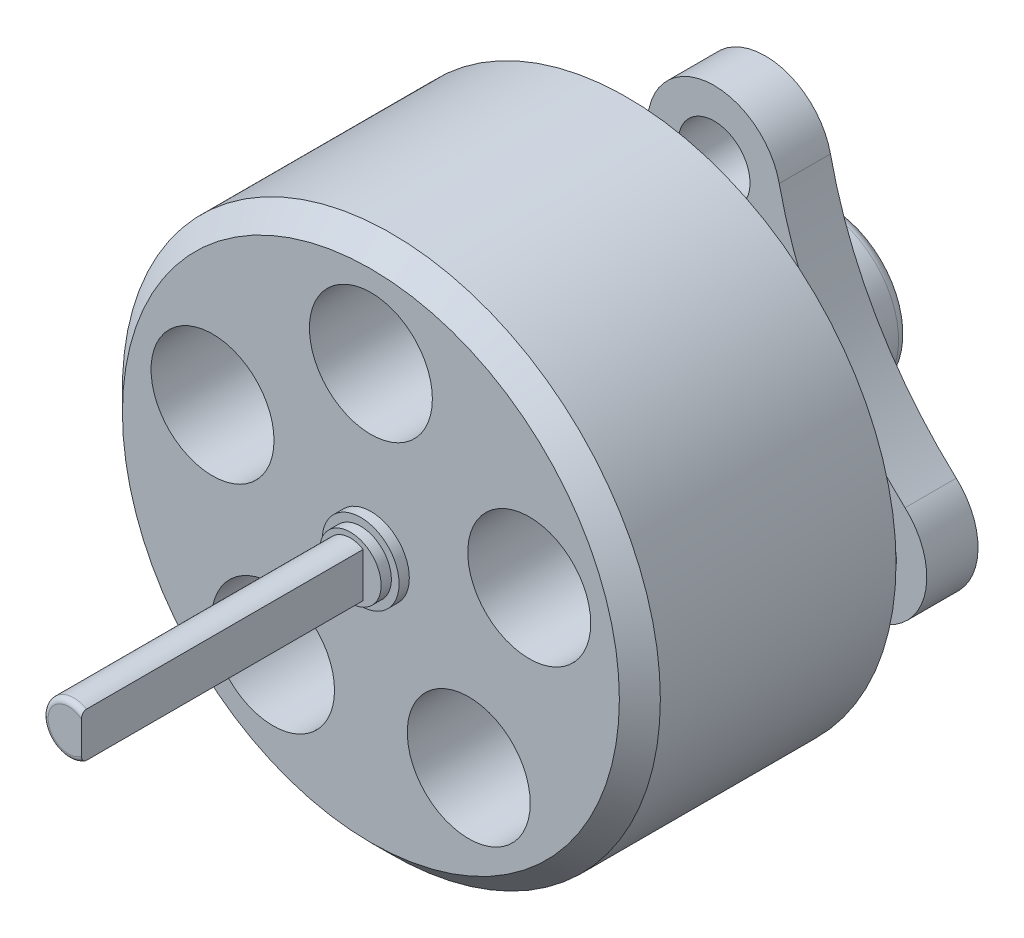
SolidWorks part; units mm, degrees
ref_plane "前视基准面" through (0, 0, 0) normal (0, 0, 1) x (1, 0, 0)
ref_plane "上视基准面" through (0, 0, 0) normal (0, 1, 0) x (1, 0, 0)
ref_plane "右视基准面" through (0, 0, 0) normal (1, 0, 0) x (0, 0, -1)
sketch "草图1" plane through (0, 0, 0) normal (0, 0, 1) x (1, 0, 0)
  circle A0 centre (0, 0) radius 5.25
  dimension "D1" = 10.5
extrude "凸台-拉伸1" add sketch "草图1" along normal blind 5
chamfer "倒角1" distance 0.4 angle 45 1 edges at (5.25, 0, 5)
sketch "草图2" plane through (0, 0, 5) normal (0, 0, 1) x (1, 0, 0)
  circle A0 centre (0, 3.25) radius 1.2
  circle A1 centre (0, 0) radius 3.25 construction
  circle A2 centre (3.0909, 1.0043) radius 1.2
  circle A3 centre (1.9103, -2.6293) radius 1.2
  circle A4 centre (-1.9103, -2.6293) radius 1.2
  circle A5 centre (-3.0909, 1.0043) radius 1.2
  point P15 (0, 0)
  dimension "D1" = 2.4
  dimension "D2" = 6.5
  dimension "D3" = 5
extrude "切除-拉伸1" cut sketch "草图2" against normal blind 2.5
sketch "草图3" plane through (0, 0, 5) normal (0, 0, 1) x (1, 0, 0)
  circle A0 centre (0, 0) radius 0.75
  dimension "D1" = 1.5
extrude "凸台-拉伸2" add sketch "草图3" along normal blind 0.2
sketch "草图4" plane through (0, 0, 5.2) normal (0, 0, 1) x (1, 0, 0)
  circle A0 centre (0, 0) radius 0.6
  dimension "D1" = 1.2
extrude "凸台-拉伸3" add sketch "草图4" along normal blind 0.2
sketch "草图5" plane through (0, 0, 5.4) normal (0, 0, 1) x (1, 0, 0)
  circle A0 centre (0, 0) radius 0.5
  dimension "D1" = 1
extrude "凸台-拉伸4" add sketch "草图5" along normal blind 5.5
fillet "圆角1" radius 0.1 1 edges at (0.5, 0, 10.9)
sketch "草图6" plane through (0, 0, 0) normal (0, 0, -1) x (-1, 0, 0)
  circle A0 centre (0, 0) radius 2.5
  dimension "D1" = 5
extrude "凸台-拉伸5" add sketch "草图6" along normal blind 1.7
sketch "草图7" plane through (0, 0, -1.7) normal (0, 0, -1) x (-1, 0, 0)
  arc A1 (3.2746, -0.4084) -> (3.1443, -1.0018) centre (0, 0) ccw construction
  arc A6 (1.2702, 3.5768) -> (-1.2702, 3.5768) centre (0, 3.3) ccw
  arc A7 (-3.7253, -0.6756) -> (-1.2702, 3.5768) centre (-9.157, 5.2953) ccw
  arc A8 (-3.7253, -0.6756) -> (-2.4551, -2.8756) centre (-2.8505, -1.6372) ccw
  arc A9 (2.4551, -2.8756) -> (3.7253, -0.6756) centre (2.8505, -1.6372) ccw
  arc A11 (1.2702, 3.5768) -> (3.7253, -0.6756) centre (9.157, 5.2953) ccw
  arc A12 (2.4551, -2.8756) -> (-2.4551, -2.8756) centre (0, -10.565) ccw
  point P12 (0, 0.0085)
  point P26 (0, 0.0085)
  dimension "D2" = 6.6
  dimension "D3" = 3
extrude "凸台-拉伸6" add sketch "草图7" along normal blind 1
sketch "草图8" plane through (0, 0, -2.7) normal (0, 0, -1) x (-1, 0, 0)
  circle A0 centre (0, 0) radius 3.3 construction
  circle A1 centre (0, 3.3) radius 0.7
  circle A2 centre (2.8579, -1.65) radius 0.7
  circle A3 centre (-2.8579, -1.65) radius 0.7
  point P12 (0, 0)
  dimension "D1" = 3
extrude "切除-拉伸2" cut sketch "草图8" against normal blind 1
sketch "草图9" plane through (0, 0, -2.7) normal (0, 0, -1) x (-1, 0, 0)
  circle A0 centre (0, 0) radius 1.5
extrude "凸台-拉伸7" add sketch "草图9" along normal blind 1.3
fillet "圆角2" radius 0.2 1 edges at (-1.5, 0, -4)
sketch "草图10" plane through (0, 0, 10.9) normal (0, 0, 1) x (1, 0, 0)
  line L0 (0.25, 0.4416) -> (0.25, -0.4416)
  arc A0 (0.25, -0.4416) -> (0.25, 0.4416) centre (0, 0) ccw
  dimension "D1" = 0.25
extrude "切除-拉伸3" cut sketch "草图10" against normal blind 5.5
